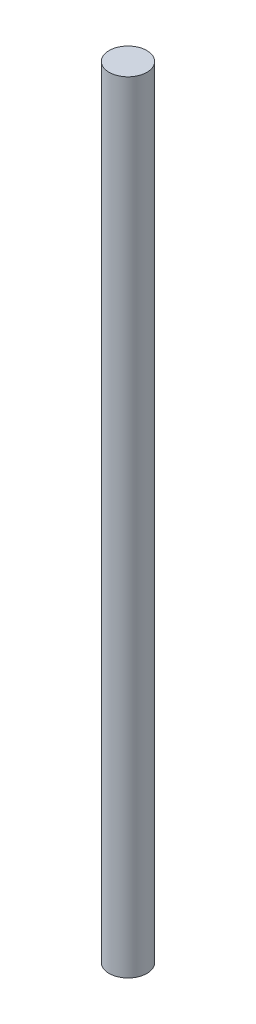
SolidWorks part; units mm, degrees
ref_plane "前视基准面" through (0, 0, 0) normal (0, 0, 1) x (1, 0, 0)
ref_plane "上视基准面" through (0, 0, 0) normal (0, 1, 0) x (1, 0, 0)
ref_plane "右视基准面" through (0, 0, 0) normal (1, 0, 0) x (0, 0, -1)
sketch "草图1" plane through (0, 0, 0) normal (0, 1, 0) x (1, 0, 0)
  circle A0 centre (0, 0) radius 15
  dimension "D1" = 30
extrude "凸台-拉伸1" add sketch "草图1" along normal mid plane 620
